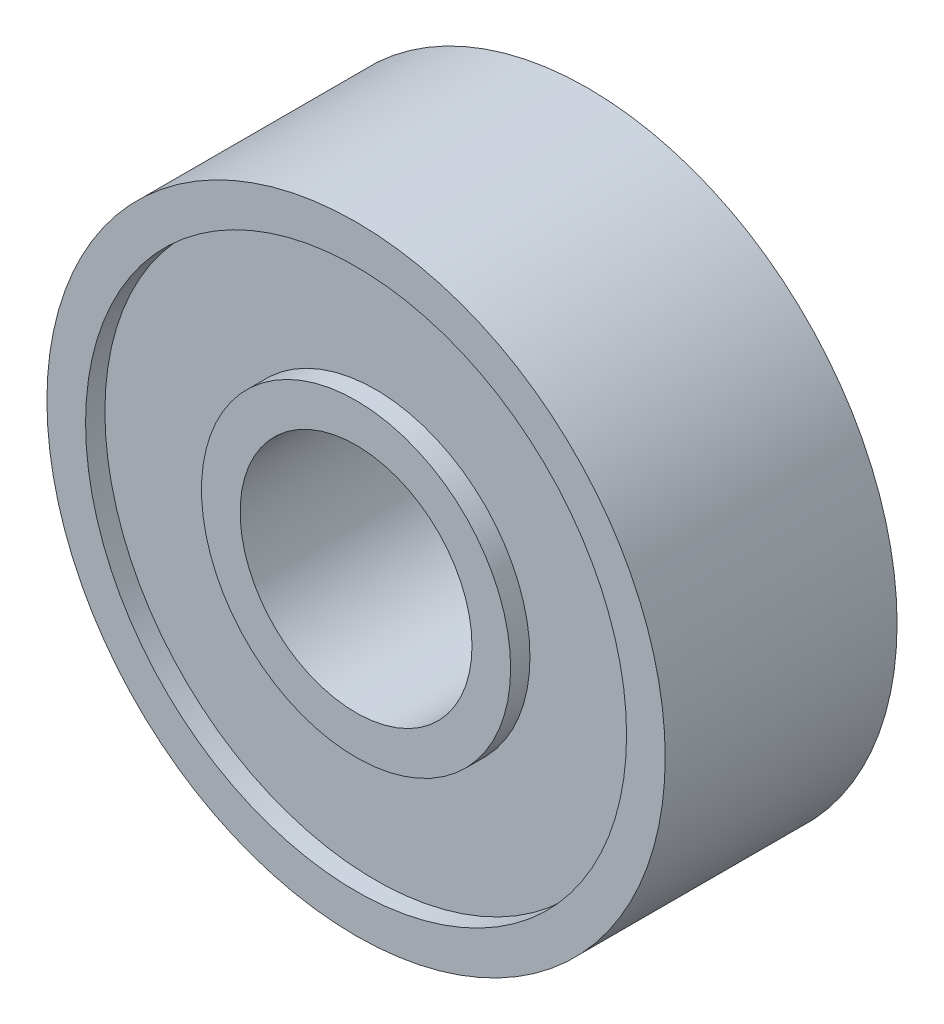
SolidWorks part; units mm, degrees
ref_plane "Front Plane" through (0, 0, 0) normal (0, 0, 1) x (1, 0, 0)
ref_plane "Top Plane" through (0, 0, 0) normal (0, 1, 0) x (1, 0, 0)
ref_plane "Right Plane" through (0, 0, 0) normal (1, 0, 0) x (0, 0, -1)
sketch "Sketch1" plane through (0, 0, 0) normal (0, 0, 1) x (1, 0, 0)
  circle A0 centre (0, 0) radius 3
  circle A1 centre (0, 0) radius 8
  dimension "D1" = 16
  dimension "D2" = 6
extrude "Boss-Extrude1" add sketch "Sketch1" along normal mid plane 6
sketch "Sketch2" plane through (0, 0, 3) normal (0, 0, 1) x (1, 0, 0)
  circle A2 centre (0, 0) radius 7
  circle A3 centre (0, 0) radius 7
  circle A5 centre (0, 0) radius 4
  circle A6 centre (0, 0) radius 4
  dimension "D1" = 1
  dimension "D2" = 1
extrude "Cut-Extrude1" cut sketch "Sketch2" against normal blind 0.5
mirror "Mirror1" about plane through (0, 0, 0) normal (0, 0, 1) of "Cut-Extrude1"
